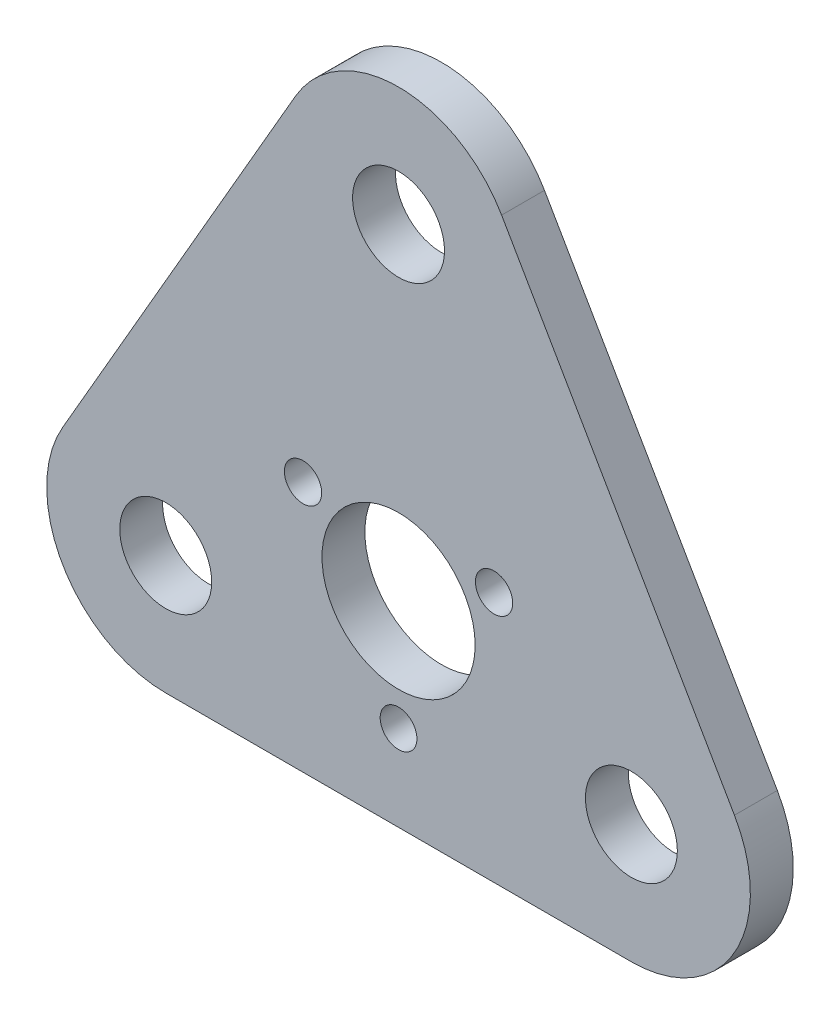
SolidWorks part; units mm, degrees
ref_plane "Front Plane" through (0, 0, 0) normal (0, 0, 1) x (1, 0, 0)
ref_plane "Top Plane" through (0, 0, 0) normal (0, 1, 0) x (1, 0, 0)
ref_plane "Right Plane" through (0, 0, 0) normal (1, 0, 0) x (0, 0, -1)
sketch "Sketch1" plane through (0, 0, 0) normal (0, 0, 1) x (1, 0, 0)
  line L1 (-16.8197, 55.1954) -> (-54.8197, -10.6225)
  line L2 (-38, -39.755) -> (38, -39.755)
  line L3 (54.8197, -10.6225) -> (16.8197, 55.1954)
  line L4 (0, -25.755) -> (0, -28.7583) construction
  circle A0 centre (0, 45.4846) radius 7.5
  arc A1 (38, -39.755) -> (54.8197, -10.6225) centre (38, -20.3333) ccw
  arc A2 (-54.8197, -10.6225) -> (-38, -39.755) centre (-38, -20.3333) ccw
  arc A3 (-16.8197, 55.1954) -> (16.8197, 55.1954) centre (0, 45.4846) cw
  circle A4 centre (38, -20.3333) radius 7.5
  circle A5 centre (-38, -20.3333) radius 7.5
  circle A6 centre (0, -7.755) radius 12.5
  circle A7 centre (0, -25.755) radius 3
  circle A9 centre (-15.5885, 1.245) radius 3.0427
  circle A10 centre (15.5885, 1.245) radius 3.0427
  point P12 (0, 84.328)
  dimension "D2" = 38
  dimension "D3" = 15
  dimension "D4" = 15
  dimension "D5" = 25
  dimension "D6" = 6
  dimension "D1" = 76
  dimension "D7" = 18
  dimension "D8" = 32
extrude "Boss-Extrude1" add sketch "Sketch1" along normal blind 7
